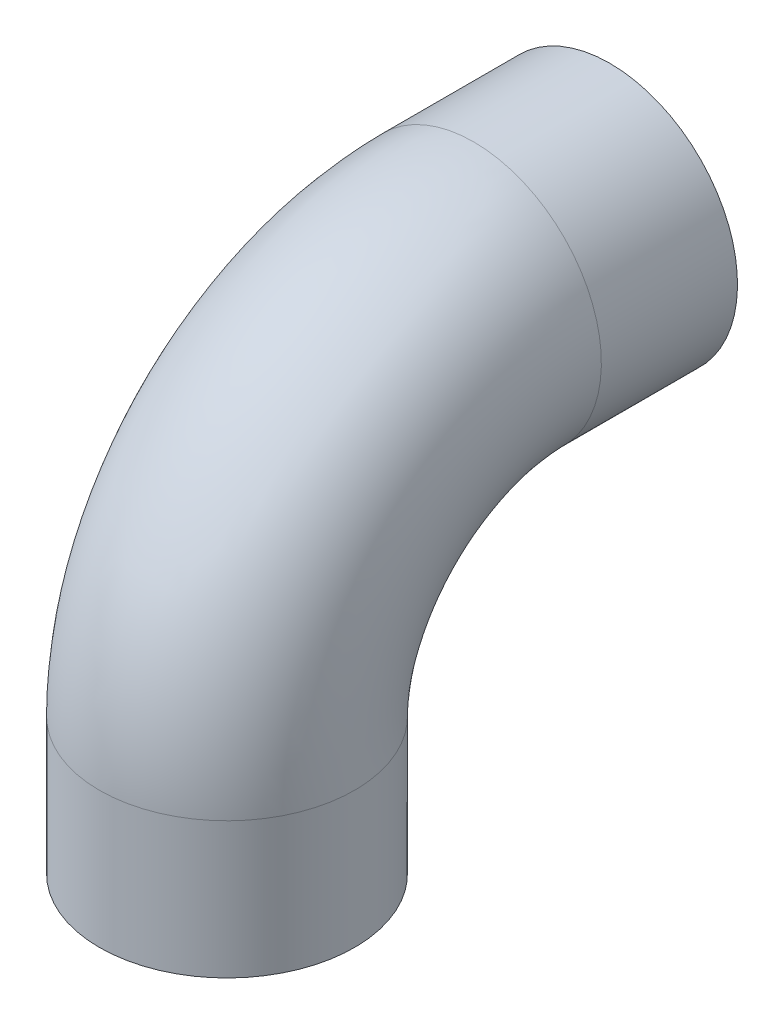
SolidWorks part; units mm, degrees
ref_plane "Front Plane" through (0, 0, 0) normal (0, 0, 1) x (1, 0, 0)
ref_plane "Top Plane" through (0, 0, 0) normal (0, 1, 0) x (1, 0, 0)
ref_plane "Right Plane" through (0, 0, 0) normal (1, 0, 0) x (0, 0, -1)
sketch "Sketch1" plane through (0, 0, 0) normal (0, 1, 0) x (1, 0, 0)
  circle A0 centre (0, 0) radius 14.2875
  circle A1 centre (0, 0) radius 10.668
  dimension "D1" = 28.575
  dimension "D2" = 21.336
sketch "Sketch2" plane through (0, 0, 0) normal (1, 0, 0) x (0, 0, -1)
  line L0 (0, 0) -> (0, 15.24)
  line L1 (27.6225, 42.8625) -> (42.8625, 42.8625)
  arc A0 (0, 15.24) -> (27.6225, 42.8625) centre (27.6225, 15.24) cw
  point P6 (0, 42.8625)
  point P7 (0.9842, 31.75)
  point P8 (0, 0)
  point P9 (0, 0)
  dimension "D3" = 15.24
  dimension "D1" = 42.8625
  dimension "D2" = 42.8625
sweep "Sweep1" add profiles "Sketch1" path "Sketch2"
sketch "Sketch3" plane through (0, 0, 0) normal (1, 0, 0) x (0, 0, -1)
  line L0 (27.6225, 57.15) -> (42.8625, 57.15) construction
